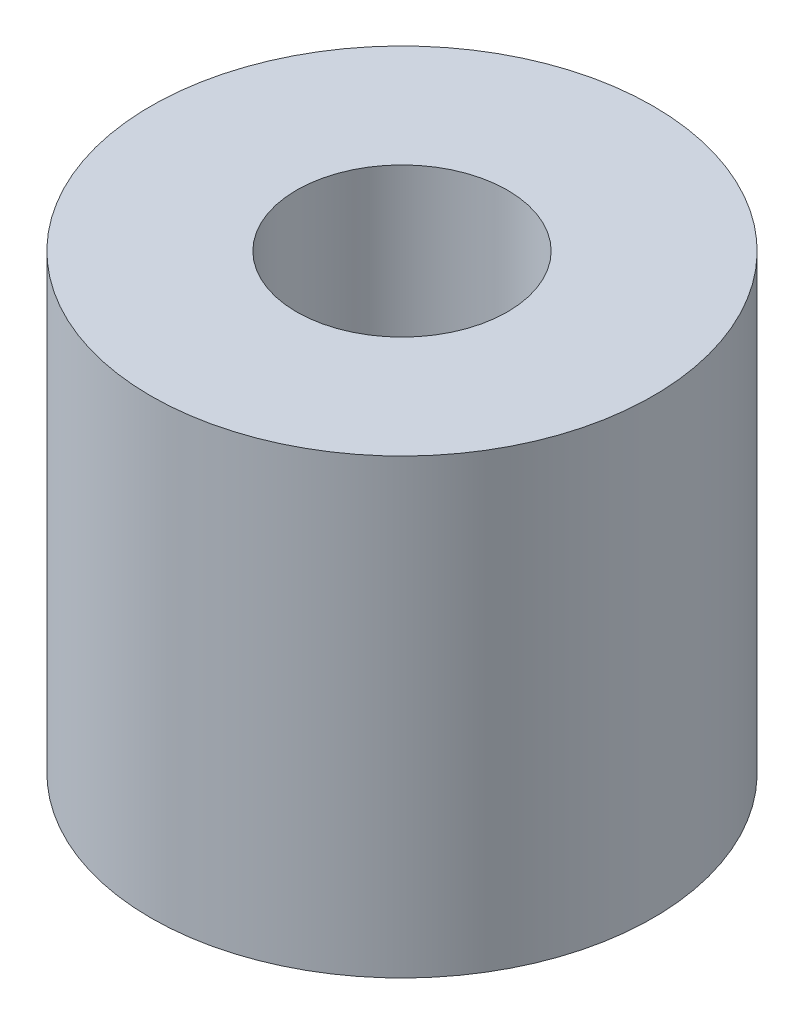
SolidWorks part; units mm, degrees
ref_plane "Płaszczyzna przednia" through (0, 0, 0) normal (0, 0, 1) x (1, 0, 0)
ref_plane "Płaszczyzna górna" through (0, 0, 0) normal (0, 1, 0) x (1, 0, 0)
ref_plane "Płaszczyzna prawa" through (0, 0, 0) normal (1, 0, 0) x (0, 0, -1)
sketch "Szkic1" plane through (0, 0, 0) normal (0, 1, 0) x (1, 0, 0)
  circle A0 centre (0, 0) radius 2.1
  circle A1 centre (0, 0) radius 5
  dimension "D1" = 4.2
  dimension "D2" = 10
extrude "Dodanie-wyciągnięcie1" add sketch "Szkic1" along normal blind 9
